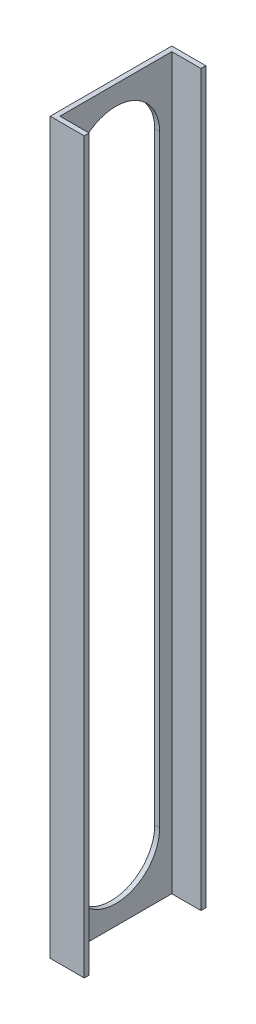
SolidWorks part; units mm, degrees
ref_plane "前视基准面" through (0, 0, 0) normal (0, 0, 1) x (1, 0, 0)
ref_plane "上视基准面" through (0, 0, 0) normal (0, 1, 0) x (1, 0, 0)
ref_plane "右视基准面" through (0, 0, 0) normal (1, 0, 0) x (0, 0, -1)
sketch "草图1" plane through (0, 0, 0) normal (0, 1, 0) x (1, 0, 0)
  line L0 (0, 0) -> (0, 50)
  line L1 (0, 50) -> (14, 50)
  line L2 (0, 0) -> (14, 0)
  line L3 (2, 2) -> (14, 2)
  line L4 (2, 2) -> (2, 48)
  line L5 (2, 48) -> (14, 48)
  line L6 (14, 50) -> (14, 48)
  line L7 (14, 2) -> (14, 0)
  dimension "D1" = 14
  dimension "D2" = 50
  dimension "D3" = 2
extrude "凸台-拉伸1" add sketch "草图1" along normal blind 300
sketch "草图2" plane through (0, 0, 0) normal (-1, 0, 0) x (0, 0, 1)
  line L0 (-25, 274) -> (-25, 26) construction
  line L1 (-7, 274) -> (-7, 26)
  line L2 (-43, 274) -> (-43, 26)
  line L3 (-50, 300) -> (0, 300) construction
  line L4 (-50, 0) -> (0, 0) construction
  arc A0 (-7, 274) -> (-43, 274) centre (-25, 274) ccw
  arc A1 (-43, 26) -> (-7, 26) centre (-25, 26) ccw
  point P2 (-25, 150)
  point P7 (0, 0)
  point P12 (-25, 0)
  point P13 (0, 0)
  dimension "D3" = 18
  dimension "D1" = 26
  dimension "D2" = 26
extrude "切除-拉伸1" cut sketch "草图2" against normal through all
